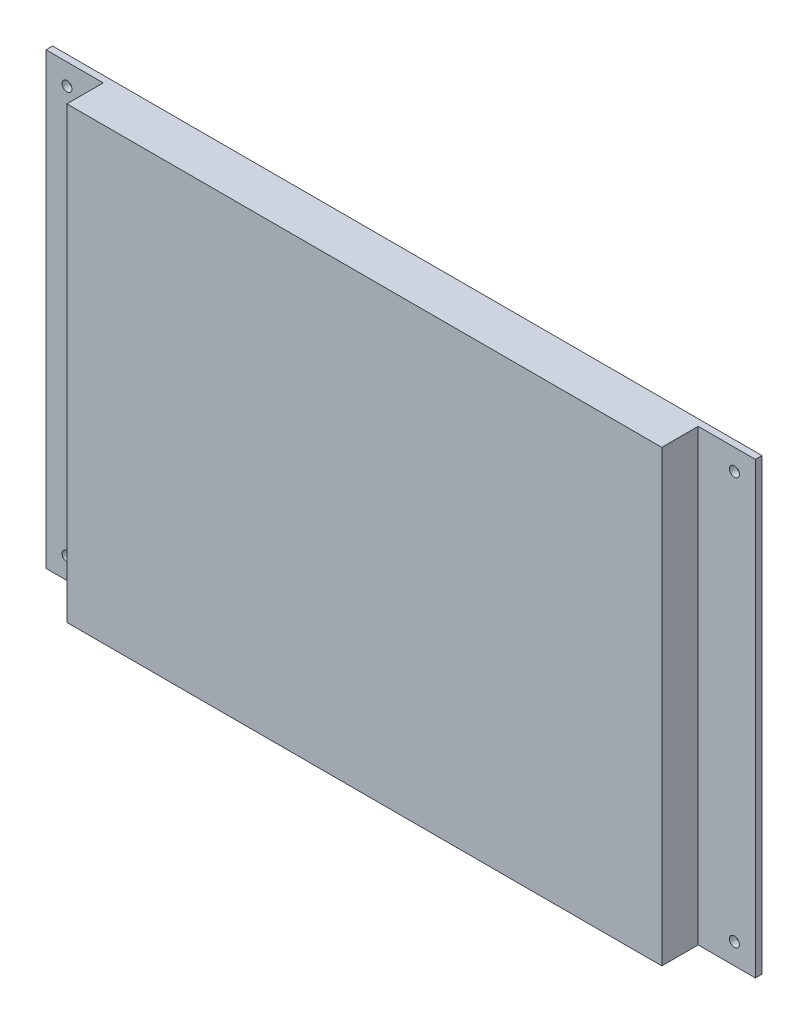
SolidWorks part; units mm, degrees
ref_plane "정면" through (0, 0, 0) normal (0, 0, 1) x (1, 0, 0)
ref_plane "윗면" through (0, 0, 0) normal (0, 1, 0) x (1, 0, 0)
ref_plane "우측면" through (0, 0, 0) normal (1, 0, 0) x (0, 0, -1)
sketch "스케치1" plane through (0, 0, 0) normal (0, 0, 1) x (1, 0, 0)
  line L0 (-128.6403, 0) -> (166.2402, 0) construction
  line L1 (-107.315, -67.945) -> (107.315, -67.945)
  line L2 (-107.315, -67.945) -> (-107.315, 67.945)
  line L3 (-107.315, 67.945) -> (107.315, 67.945)
  line L4 (107.315, -67.945) -> (107.315, 67.945)
  line L5 (121.5438, 61.595) -> (-143.6988, 61.595) construction
  line L6 (0, -114.758) -> (0, 114.0212) construction
  line L8 (-143.6988, -61.595) -> (125.3427, -61.595) construction
  circle A0 centre (100.965, 61.595) radius 1.5
  circle A1 centre (100.965, -61.595) radius 1.5
  circle A2 centre (-100.965, -61.595) radius 1.5
  circle A3 centre (-100.965, 61.595) radius 1.5
  point P0 (0, 0)
  point P20 (0, 0)
  point P23 (0, 0)
  point P24 (0, 0)
  point P25 (0, 0)
  point P26 (0, 0)
  dimension "D3" = 3
  dimension "D4" = 123.19
  dimension "D8" = 6.35
  dimension "D9" = 6.35
  dimension "D1" = 214.63
  dimension "D2" = 135.89
  dimension "D5" = 67.945
  dimension "D6" = 107.315
  dimension "D7" = 61.595
extrude "보스-돌출1" add sketch "스케치1" along normal blind 2
sketch "스케치2" plane through (0, 0, 2) normal (0, 0, 1) x (1, 0, 0)
  line L0 (-136.0119, 0) -> (169.849, 0) construction
  line L1 (-107.315, -67.945) -> (107.315, -67.945) construction
  line L2 (0, 83.9293) -> (0, -80.8331) construction
  line L3 (-90, -67.945) -> (90, -67.945)
  line L4 (-90, -67.945) -> (-90, 67.945)
  line L5 (-90, 67.945) -> (90, 67.945)
  line L6 (90, -67.945) -> (90, 67.945)
  line L7 (107.315, 67.945) -> (-107.315, 67.945) construction
  point P9 (59.0491, 42.1305)
  point P10 (-62.8088, -67.945)
  point P13 (71.2127, 67.945)
  dimension "D1" = 180
  dimension "D2" = 90
extrude "보스-돌출2" add sketch "스케치2" along normal blind 11
